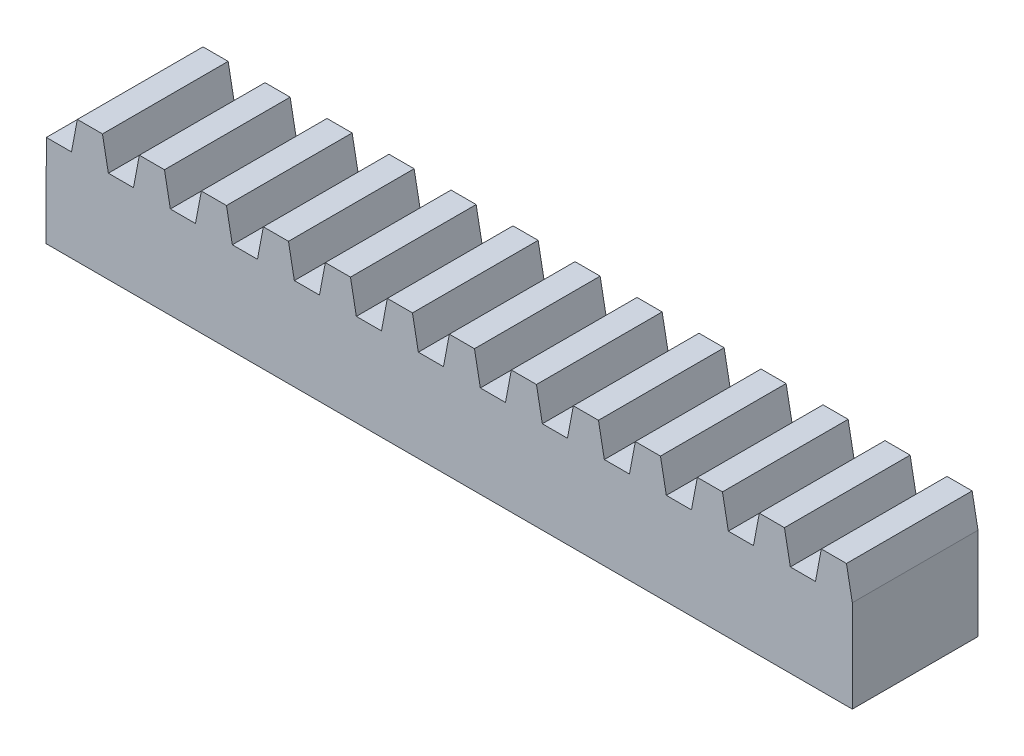
SolidWorks part; units mm, degrees
ref_plane "Спереди" through (0, 0, 0) normal (0, 0, 1) x (1, 0, 0)
ref_plane "Сверху" through (0, 0, 0) normal (0, 1, 0) x (1, 0, 0)
ref_plane "Справа" through (0, 0, 0) normal (1, 0, 0) x (0, 0, -1)
sketch "Эскиз8" plane through (0, 0, 0) normal (0, 0, 1) x (1, 0, 0)
  line L0 (0, 0) -> (0, 11)
  line L13 (-96.2407, 0) -> (0, 0)
  line L22 (-0.7, 14.71) -> (-3.7, 14.71)
  line L23 (-4.4, 11) -> (-7.4, 11)
  line L24 (-4.4, 11) -> (-3.7, 14.71)
  line L25 (-0.7, 14.71) -> (0, 11)
  line L26 (-96.2, 11) -> (-96.2407, 0)
  line L27 (-8.1, 14.71) -> (-11.1, 14.71)
  line L28 (-11.8, 11) -> (-14.8, 11)
  line L29 (-11.8, 11) -> (-11.1, 14.71)
  line L30 (-8.1, 14.71) -> (-7.4, 11)
  line L31 (-15.5, 14.71) -> (-18.5, 14.71)
  line L32 (-19.2, 11) -> (-22.2, 11)
  line L33 (-19.2, 11) -> (-18.5, 14.71)
  line L34 (-15.5, 14.71) -> (-14.8, 11)
  line L35 (-22.9, 14.71) -> (-25.9, 14.71)
  line L36 (-26.6, 11) -> (-29.6, 11)
  line L37 (-26.6, 11) -> (-25.9, 14.71)
  line L38 (-22.9, 14.71) -> (-22.2, 11)
  line L39 (-45.1, 14.71) -> (-48.1, 14.71)
  line L40 (-48.8, 11) -> (-51.8, 11)
  line L41 (-48.8, 11) -> (-48.1, 14.71)
  line L42 (-45.1, 14.71) -> (-44.4, 11)
  line L43 (-30.3, 14.71) -> (-33.3, 14.71)
  line L44 (-34, 11) -> (-37, 11)
  line L45 (-34, 11) -> (-33.3, 14.71)
  line L46 (-30.3, 14.71) -> (-29.6, 11)
  line L47 (-37.7, 14.71) -> (-40.7, 14.71)
  line L48 (-41.4, 11) -> (-44.4, 11)
  line L49 (-41.4, 11) -> (-40.7, 14.71)
  line L50 (-37.7, 14.71) -> (-37, 11)
  line L51 (-59.9, 14.71) -> (-62.9, 14.71)
  line L52 (-63.6, 11) -> (-66.6, 11)
  line L53 (-63.6, 11) -> (-62.9, 14.71)
  line L54 (-59.9, 14.71) -> (-59.2, 11)
  line L55 (-82.1, 14.71) -> (-85.1, 14.71)
  line L56 (-85.8, 11) -> (-88.8, 11)
  line L57 (-85.8, 11) -> (-85.1, 14.71)
  line L58 (-82.1, 14.71) -> (-81.4, 11)
  line L59 (-67.3, 14.71) -> (-70.3, 14.71)
  line L60 (-71, 11) -> (-74, 11)
  line L61 (-71, 11) -> (-70.3, 14.71)
  line L62 (-67.3, 14.71) -> (-66.6, 11)
  line L63 (-74.7, 14.71) -> (-77.7, 14.71)
  line L64 (-78.4, 11) -> (-81.4, 11)
  line L65 (-78.4, 11) -> (-77.7, 14.71)
  line L66 (-74.7, 14.71) -> (-74, 11)
  line L67 (-52.5, 14.71) -> (-55.5, 14.71)
  line L68 (-56.2, 11) -> (-59.2, 11)
  line L69 (-56.2, 11) -> (-55.5, 14.71)
  line L70 (-52.5, 14.71) -> (-51.8, 11)
  line L71 (-89.5, 14.71) -> (-92.5, 14.71)
  line L72 (-93.2, 11) -> (-96.2, 11)
  line L73 (-93.2, 11) -> (-92.5, 14.71)
  line L74 (-89.5, 14.71) -> (-88.8, 11)
extrude "Бобышка-Вытянуть4" add sketch "Эскиз8" along normal blind 15
